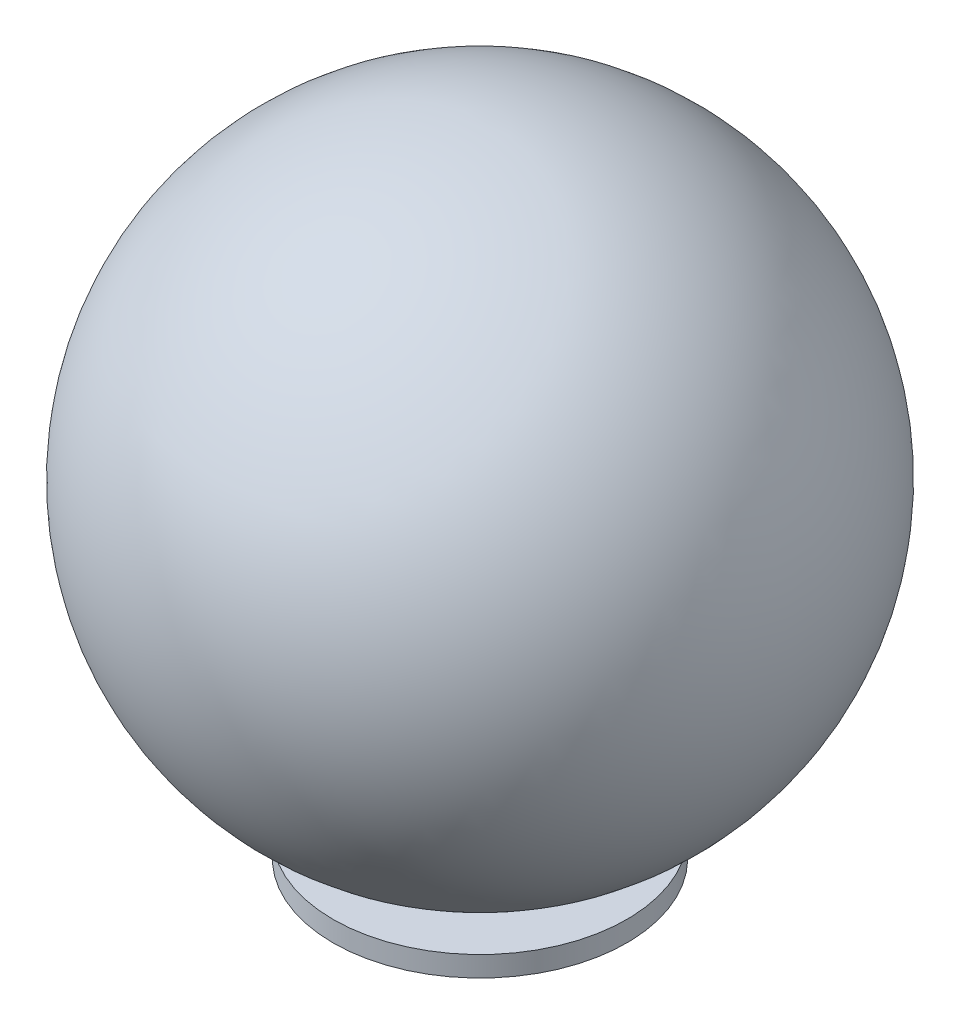
SolidWorks part; units mm, degrees
ref_plane "Front Plane" through (0, 0, 0) normal (0, 0, 1) x (1, 0, 0)
ref_plane "Top Plane" through (0, 0, 0) normal (0, 1, 0) x (1, 0, 0)
ref_plane "Right Plane" through (0, 0, 0) normal (1, 0, 0) x (0, 0, -1)
sketch "Sketch1" plane through (0, 0, 0) normal (0, 0, 1) x (1, 0, 0)
  line L0 (0, 150.4568) -> (0, 144.6782) construction
  line L1 (0, 150.4568) -> (0, 144.6782)
  line L2 (0, -144.6782) -> (0, -150.4568) construction
  line L3 (0, -144.6782) -> (0, -150.4568)
  line L4 (0, 150.4568) -> (0, -150.4568) construction
  arc A0 (0, 150.4568) -> (0, -150.4568) centre (0, 0) ccw
  arc A1 (0, 144.6782) -> (0, -144.6782) centre (0, 0) ccw
revolve "Revolve1" add sketch "Sketch1" angle 360 about L0
ref_plane "Plane1" through (0, -151, 0) normal (0, 1, 0) x (1, 0, 0)
sketch "Sketch2" plane through (0, -151, 0) normal (0, 1, 0) x (1, 0, 0)
  circle A0 centre (0, 0) radius 72.0864
extrude "Boss-Extrude1" add sketch "Sketch2" against normal blind 10 separate body
